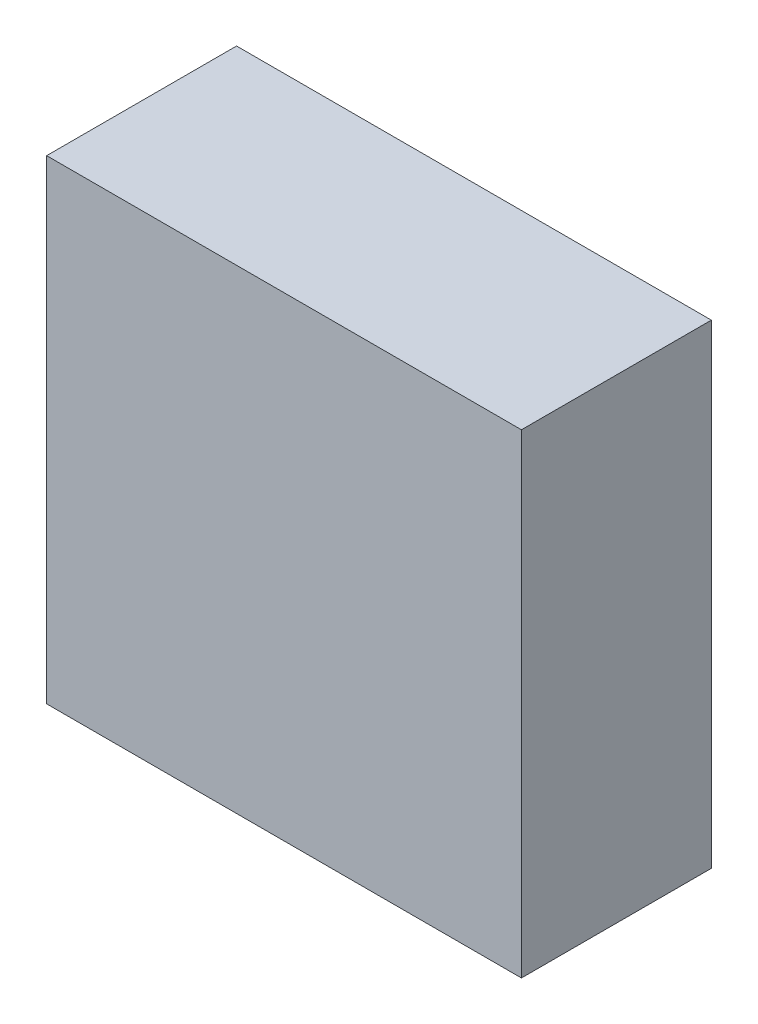
SolidWorks part; units mm, degrees
ref_plane "正面" through (0, 0, 0) normal (0, 0, 1) x (1, 0, 0)
ref_plane "平面" through (0, 0, 0) normal (0, 1, 0) x (1, 0, 0)
ref_plane "右側面" through (0, 0, 0) normal (1, 0, 0) x (0, 0, -1)
sketch "ｽｹｯﾁ2" plane through (0, 0, 0) normal (0, 0, 1) x (1, 0, 0)
  line L1 (0, 0) -> (1000, 0)
  line L2 (0, 0) -> (0, 1000)
  line L3 (0, 1000) -> (1000, 1000)
  line L4 (1000, 0) -> (1000, 1000)
  dimension "D1" = 1000
  dimension "D2" = 1000
extrude "ﾎﾞｽ - 押し出し1" add sketch "ｽｹｯﾁ2" along normal blind 400
